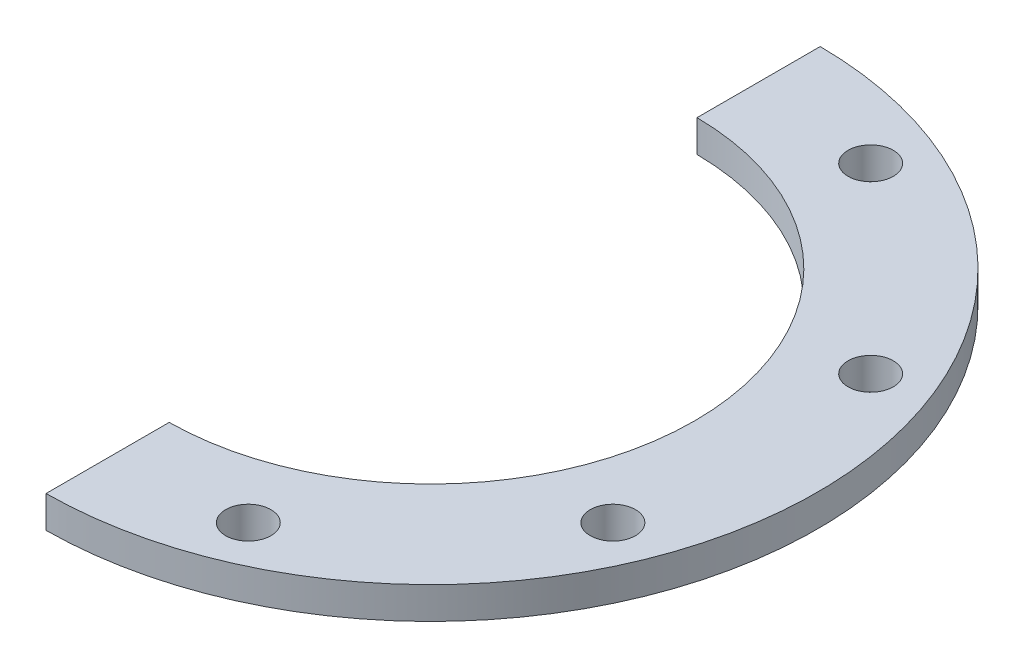
SolidWorks part; units mm, degrees
other "DetailItem1"
other "DetailItem2"
other "DetailItem3"
material "AISI 316 Stainless Steel Sheet (SS)"
ref_plane "Front Plane" through (0, 0, 0) normal (0, 0, 1) x (1, 0, 0)
ref_plane "Top Plane" through (0, 0, 0) normal (0, 1, 0) x (1, 0, 0)
ref_plane "Right Plane" through (0, 0, 0) normal (1, 0, 0) x (0, 0, -1)
ref_plane "40K Bottom Cold head Location" through (0, 87.18, 0) normal (0, 1, 0) x (1, 0, 0)
ref_plane "Top_Connection_Plane" through (34.5, 0, 0) normal (1, 0, 0) x (0, 0, -1)
ref_plane "Bottom_Connection_Plane" through (80.58, 0, 0) normal (1, 0, 0) x (0, 0, -1)
sketch "Sketch2" plane through (0, 87.18, 0) normal (0, 1, 0) x (1, 0, 0)
  line L0 (0, 26) -> (0, -26) construction
  line L1 (0, 0) -> (12.8199, 30.95) construction
  line L2 (0.25, 38.4992) -> (0.25, 26.2488)
  line L3 (0.25, -38.4992) -> (0.25, -26.2488)
  line L4 (-12.8199, 30.95) -> (0, 0) construction
  line L5 (-0.25, 38.4992) -> (-0.25, 26.2488)
  line L6 (-28.5, 43.4992) -> (28.5, 43.4992)
  line L7 (-38.5, 33.4992) -> (-38.5, -33.4992)
  line L8 (-28.5, -43.4992) -> (28.5, -43.4992)
  line L9 (38.5, 33.4992) -> (38.5, -33.4992)
  line L10 (-0.25, -26.2488) -> (-0.25, -38.4992)
  line L11 (22.0842, 33.4992) -> (25.2921, 27.9429) construction
  line L12 (25.2921, 27.9429) -> (31.7079, 27.9429) construction
  line L13 (31.7079, 27.9429) -> (34.9158, 33.4992) construction
  line L14 (34.9158, 33.4992) -> (31.7079, 39.0554) construction
  line L15 (31.7079, 39.0554) -> (25.2921, 39.0554) construction
  line L16 (25.2921, 39.0554) -> (22.0842, 33.4992) construction
  line L17 (25.2921, 39.0554) -> (31.7079, 27.9429) construction
  line L18 (0.25, 38.4992) -> (0.25, 43.4992)
  line L19 (-0.25, 38.4992) -> (-0.25, 43.4992)
  line L20 (0.25, -38.4992) -> (0.25, -43.4992)
  line L21 (-0.25, -38.4992) -> (-0.25, -43.4992)
  circle A0 centre (0, 0) radius 26
  circle A1 centre (12.8199, 30.95) radius 2.25
  circle A2 centre (30.95, 12.8199) radius 2.25
  circle A3 centre (30.95, -12.8199) radius 2.25
  circle A4 centre (12.8199, -30.95) radius 2.25
  circle A5 centre (-12.8199, -30.95) radius 2.25 [skipped]
  circle A6 centre (-30.95, -12.8199) radius 2.25 [skipped]
  circle A7 centre (-30.95, 12.8199) radius 2.25 [skipped]
  circle A8 centre (-12.8199, 30.95) radius 2.25 [skipped]
  circle A9 centre (0, 0) radius 38.5
  circle A10 centre (0, 0) radius 26.25
  circle A11 centre (-12.8199, -30.95) radius 2.25
  circle A12 centre (-30.95, -12.8199) radius 2.25
  circle A13 centre (-30.95, 12.8199) radius 2.25
  circle A14 centre (-12.8199, 30.95) radius 2.25
  circle A15 centre (-28.5, 33.4992) radius 3.2639
  circle A16 centre (28.5, 33.4992) radius 3.2639
  circle A17 centre (-28.5, -33.4992) radius 3.2639
  circle A18 centre (28.5, -33.4992) radius 3.2639
  circle A19 centre (28.5, 33.4992) radius 4.7625 construction
  circle A20 centre (28.5, 33.4992) radius 2.3269 construction
  arc A21 (-38.5, -33.4992) -> (-28.5, -43.4992) centre (-28.5, -33.4992) ccw
  arc A22 (28.5, -43.4992) -> (38.5, -33.4992) centre (28.5, -33.4992) ccw
  arc A23 (-28.5, 43.4992) -> (-38.5, 33.4992) centre (-28.5, 33.4992) ccw
  arc A24 (28.5, 43.4992) -> (38.5, 33.4992) centre (28.5, 33.4992) cw
  point P25 (0, 0)
  dimension "D1" = 52
  dimension "D3" = 4.5
  dimension "D8" = 77
  dimension "D9" = 52.5
  dimension "D13" = 6.5278
  dimension "D20" = 9.525
  dimension "D24" = 10
  dimension "D2" = 33.5
  dimension "D4" = 22.5
  dimension "D6" = 33.5
  dimension "D7" = 33.5
  dimension "D10" = 0.25
  dimension "D11" = 5
  dimension "D12" = 5
  dimension "D14" = 10
  dimension "D15" = 10
  dimension "D16" = 10
  dimension "D17" = 10
  dimension "D18" = 5
  dimension "D19" = 0.25
  dimension "D21" = 11.1125
  dimension "D22" = 11.1125
  dimension "D23" = 11.1125
  dimension "D5" = 8
extrude "Boss-Extrude1" add sketch "Sketch2" against normal blind 3.175 contours A10 L3 A9 L2 A4 A3 A2 A1
sketch "Sketch1" plane through (0, 0, 0) normal (0, 1, 0) x (1, 0, 0)
  line L0 (72.84, 17.5) -> (72.84, -17.5)
  line L5 (20, 12.7) -> (75, 12.7)
  line L6 (20, 12.7) -> (20, -12.7)
  line L7 (20, -12.7) -> (75, -12.7)
  line L8 (75, 12.7) -> (75, -12.7)
  line L9 (72.84, 17.5) -> (75, 17.5)
  line L10 (75, 17.5) -> (75, 12.7)
  line L11 (72.84, -17.5) -> (75, -17.5)
  line L12 (75, -17.5) -> (75, -12.7)
  circle A0 centre (23.18, 6.35) radius 1.63
  circle A1 centre (35.88, 6.35) radius 1.63
  circle A2 centre (48.58, 6.35) radius 1.63
  circle A3 centre (35.88, -6.35) radius 1.63
  circle A4 centre (48.58, -6.35) radius 1.63
  circle A5 centre (23.18, -6.35) radius 1.63
  circle A6 centre (61.28, 6.35) radius 1.63
  circle A7 centre (61.28, -6.35) radius 1.63
  point P11 (72.84, 0)
  point P12 (75, 0)
  dimension "D5" = 3.26
  dimension "55" = 55
  dimension "D2" = 25.4
  dimension "D3" = 6.35
  dimension "D4" = 3.18
  dimension "D6" = 12.7
  dimension "D7" = 12.7
  dimension "D10" = 20
  dimension "D11" = 12.7
  dimension "D12" = 35
  dimension "D13" = 2.16
  dimension "D14" = 12.7
  dimension "D8" = 3
  dimension "D9" = 2
sketch "Sketch3" plane through (0, 87.18, 0) normal (0, 1, 0) x (1, 0, 0)
  arc A0 (0.25, -38.4992) -> (0.25, 38.4992) centre (0, 0) ccw construction
  point P0 (38.5, 0)
equation "\"D7@Sketch2\"=\"D2@Sketch2\""
equation "\"D6@Sketch2\"=\"D2@Sketch2\""
equation "\"Distance_From_Cold_Center\"=20"
equation "\"D10@Sketch1\"=\"Distance_From_Cold_Center\""
equation "\"D11@Sketch1\"=\"D2@Sketch1\"/2"
equation "\"Inside_Cold_Rod_Dia\"=52"
equation "\"D1@Sketch2\"=\"Inside_Cold_Rod_Dia\""
equation "\"40K_Cold_Head_Dia\"=77"
equation "\"D8@Sketch2\"=\"40K_Cold_Head_Dia\""
equation "\"D14@Sketch1\"=\"D6@Sketch1\""
equation "\"D15@Sketch2\"=\"D14@Sketch2\""
equation "\"D16@Sketch2\"=\"D15@Sketch2\""
equation "\"D17@Sketch2\"=\"D16@Sketch2\""
equation "\"D12@Sketch2\"=\"D11@Sketch2\""
equation "\"D19@Sketch2\"=\"D10@Sketch2\""
equation "\"D22@Sketch2\"=\"D21@Sketch2\""
equation "\"D23@Sketch2\"=\"D22@Sketch2\""
